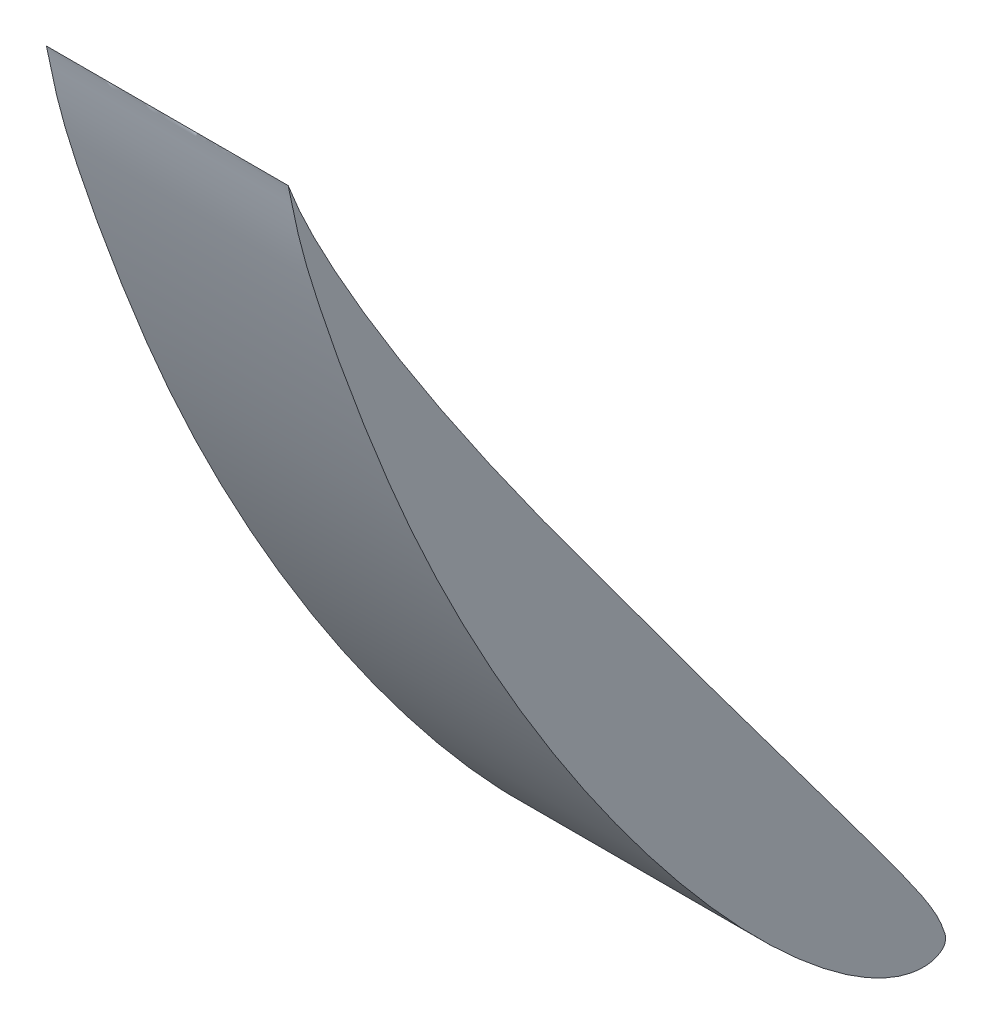
SolidWorks part; units mm, degrees
ref_plane "Front Plane" through (0, 0, 0) normal (0, 0, 1) x (1, 0, 0)
ref_plane "Top Plane" through (0, 0, 0) normal (0, 1, 0) x (1, 0, 0)
ref_plane "Right Plane" through (0, 0, 0) normal (1, 0, 0) x (0, 0, -1)
curve "Curve1"
  spline degree 3 poles (20, 28.4633, 15.8466) (20, 28.7145, 15.934) (20, 28.4668, 15.865) (20, 28.2665, 15.8303) (20, 27.805, 15.7338) (20, 27.257, 15.6261) (20, 26.5691, 15.4729) (20, 25.7774, 15.2676) (20, 24.8753, 15.0019) (20, 23.8666, 14.684) (20, 22.7562, 14.3166) (20, 21.5545, 13.9013) (20, 20.2714, 13.4406) (20, 18.9177, 12.9361) (20, 17.5049, 12.3899) (20, 16.0454, 11.8026) (20, 14.5502, 11.1748) (20, 13.0315, 10.4989) (20, 11.4963, 9.777) (20, 9.9507, 9.0131) (20, 8.4042, 8.2062) (20, 6.8625, 7.363) (20, 5.3341, 6.4857) (20, 3.8278, 5.5775) (20, 2.3494, 4.6458) (20, 0.9081, 3.6924) (20, -0.4896, 2.7237) (20, -1.8372, 1.7454) (20, -3.1273, 0.7627) (20, -4.3542, -0.2179) (20, -5.5115, -1.191) (20, -6.5931, -2.151) (20, -7.5948, -3.0911) (20, -8.5109, -4.0068) (20, -9.3378, -4.8917) (20, -10.0725, -5.7403) (20, -10.711, -6.5478) (20, -11.2536, -7.3075) (20, -11.6961, -8.0179) (20, -12.0372, -8.6743) (20, -12.2858, -9.2699) (20, -12.4349, -9.8062) (20, -12.4935, -10.273) (20, -12.4712, -10.6726) (20, -12.3544, -10.9815) (20, -12.1874, -11.2303) (20, -11.8784, -11.3083) (20, -11.5185, -11.187) (20, -11.0523, -11) (20, -10.4802, -10.6788) (20, -9.8012, -10.2446) (20, -9.0094, -9.6973) (20, -8.1049, -9.0458) (20, -7.0899, -8.2993) (20, -5.9699, -7.4667) (20, -4.7522, -6.5557) (20, -3.4437, -5.5759) (20, -2.0535, -4.5356) (20, -0.5903, -3.4444) (20, 0.9355, -2.3108) (20, 2.5131, -1.1441) (20, 4.1313, 0.0473) (20, 5.7779, 1.2578) (20, 7.4418, 2.4846) (20, 9.1179, 3.7188) (20, 10.8002, 4.9508) (20, 12.4834, 6.1624) (20, 14.1554, 7.3388) (20, 15.7997, 8.4713) (20, 17.4028, 9.5493) (20, 18.9517, 10.5634) (20, 20.4327, 11.5049) (20, 21.8324, 12.3661) (20, 23.1371, 13.1404) (20, 24.333, 13.822) (20, 25.4084, 14.4074) (20, 26.3458, 14.893) (20, 27.1456, 15.2804) (20, 27.7591, 15.5576) (20, 28.2613, 15.7594) (20, 28.4633, 15.8466) (20, 28.7145, 15.934) (20, 28.4668, 15.865) knots -0.008893 -0.003951 -0.000989 0 0.000979 0.003786 0.008179 0.01394 0.020915 0.029057 0.038414 0.048974 0.060645 0.073334 0.086939 0.101355 0.116471 0.132171 0.148332 0.16489 0.181807 0.198987 0.216369 0.233891 0.251455 0.26899 0.28641 0.303633 0.320589 0.337187 0.353353 0.369012 0.384083 0.3985 0.412191 0.425098 0.437171 0.448351 0.458606 0.467901 0.476216 0.483573 0.48997 0.495456 0.500132 0.503992 0.50723 0.509987 0.512501 0.516074 0.521095 0.527571 0.535587 0.545177 0.556302 0.568875 0.5828 0.597975 0.614286 0.631613 0.649826 0.668792 0.688371 0.708417 0.728797 0.749399 0.770146 0.790953 0.811664 0.832074 0.851999 0.871282 0.889761 0.90728 0.923686 0.938833 0.952579 0.964796 0.975365 0.984179 0.991107 0.996049 0.999011 1 1.000979 1.003786 1.008179 periodic
ref_plane "Plane1" through (20, 0, 0) normal (1, 0, 0) x (0, 0, -1)
sketch "Sketch2" plane through (20, 0, 0) normal (1, 0, 0) x (0, 0, -1)
  spline S0 degree 3 poles (-15.8466, 28.4633) (-15.934, 28.7145) (-15.865, 28.4668) (-15.8303, 28.2665) (-15.7338, 27.805) (-15.6261, 27.257) (-15.4729, 26.5691) (-15.2676, 25.7774) (-15.0019, 24.8753) (-14.684, 23.8666) (-14.3166, 22.7562) (-13.9013, 21.5545) (-13.4406, 20.2714) (-12.9361, 18.9177) (-12.3899, 17.5049) (-11.8026, 16.0454) (-11.1748, 14.5502) (-10.4989, 13.0315) (-9.777, 11.4963) (-9.0131, 9.9507) (-8.2062, 8.4042) (-7.363, 6.8625) (-6.4857, 5.3341) (-5.5775, 3.8278) (-4.6458, 2.3494) (-3.6924, 0.9081) (-2.7237, -0.4896) (-1.7454, -1.8372) (-0.7627, -3.1273) (0.2179, -4.3542) (1.191, -5.5115) (2.151, -6.5931) (3.0911, -7.5948) (4.0068, -8.5109) (4.8917, -9.3378) (5.7403, -10.0725) (6.5478, -10.711) (7.3075, -11.2536) (8.0179, -11.6961) (8.6743, -12.0372) (9.2699, -12.2858) (9.8062, -12.4349) (10.273, -12.4935) (10.6726, -12.4712) (10.9815, -12.3544) (11.2303, -12.1874) (11.3083, -11.8784) (11.187, -11.5185) (11, -11.0523) (10.6788, -10.4802) (10.2446, -9.8012) (9.6973, -9.0094) (9.0458, -8.1049) (8.2993, -7.0899) (7.4667, -5.9699) (6.5557, -4.7522) (5.5759, -3.4437) (4.5356, -2.0535) (3.4444, -0.5903) (2.3108, 0.9355) (1.1441, 2.5131) (-0.0473, 4.1313) (-1.2578, 5.7779) (-2.4846, 7.4418) (-3.7188, 9.1179) (-4.9508, 10.8002) (-6.1624, 12.4834) (-7.3388, 14.1554) (-8.4713, 15.7997) (-9.5493, 17.4028) (-10.5634, 18.9517) (-11.5049, 20.4327) (-12.3661, 21.8324) (-13.1404, 23.1371) (-13.822, 24.333) (-14.4074, 25.4084) (-14.893, 26.3458) (-15.2804, 27.1456) (-15.5576, 27.7591) (-15.7594, 28.2613) (-15.8466, 28.4633) (-15.934, 28.7145) (-15.865, 28.4668) knots -0.008893 -0.003951 -0.000989 0 0.000979 0.003786 0.008179 0.01394 0.020915 0.029057 0.038414 0.048974 0.060645 0.073334 0.086939 0.101355 0.116471 0.132171 0.148332 0.16489 0.181807 0.198987 0.216369 0.233891 0.251455 0.26899 0.28641 0.303633 0.320589 0.337187 0.353353 0.369012 0.384083 0.3985 0.412191 0.425098 0.437171 0.448351 0.458606 0.467901 0.476216 0.483573 0.48997 0.495456 0.500132 0.503992 0.50723 0.509987 0.512501 0.516074 0.521095 0.527571 0.535587 0.545177 0.556302 0.568875 0.5828 0.597975 0.614286 0.631613 0.649826 0.668792 0.688371 0.708417 0.728797 0.749399 0.770146 0.790953 0.811664 0.832074 0.851999 0.871282 0.889761 0.90728 0.923686 0.938833 0.952579 0.964796 0.975365 0.984179 0.991107 0.996049 0.999011 1 1.000979 1.003786 1.008179 only from (-15.9182, 28.6639) to (-15.9182, 28.6639) construction
  spline S1 degree 3 poles (-15.8466, 28.4633) (-15.934, 28.7145) (-15.865, 28.4668) (-15.8303, 28.2665) (-15.7338, 27.805) (-15.6261, 27.257) (-15.4729, 26.5691) (-15.2676, 25.7774) (-15.0019, 24.8753) (-14.684, 23.8666) (-14.3166, 22.7562) (-13.9013, 21.5545) (-13.4406, 20.2714) (-12.9361, 18.9177) (-12.3899, 17.5049) (-11.8026, 16.0454) (-11.1748, 14.5502) (-10.4989, 13.0315) (-9.777, 11.4963) (-9.0131, 9.9507) (-8.2062, 8.4042) (-7.363, 6.8625) (-6.4857, 5.3341) (-5.5775, 3.8278) (-4.6458, 2.3494) (-3.6924, 0.9081) (-2.7237, -0.4896) (-1.7454, -1.8372) (-0.7627, -3.1273) (0.2179, -4.3542) (1.191, -5.5115) (2.151, -6.5931) (3.0911, -7.5948) (4.0068, -8.5109) (4.8917, -9.3378) (5.7403, -10.0725) (6.5478, -10.711) (7.3075, -11.2536) (8.0179, -11.6961) (8.6743, -12.0372) (9.2699, -12.2858) (9.8062, -12.4349) (10.273, -12.4935) (10.6726, -12.4712) (10.9815, -12.3544) (11.2303, -12.1874) (11.3083, -11.8784) (11.187, -11.5185) (11, -11.0523) (10.6788, -10.4802) (10.2446, -9.8012) (9.6973, -9.0094) (9.0458, -8.1049) (8.2993, -7.0899) (7.4667, -5.9699) (6.5557, -4.7522) (5.5759, -3.4437) (4.5356, -2.0535) (3.4444, -0.5903) (2.3108, 0.9355) (1.1441, 2.5131) (-0.0473, 4.1313) (-1.2578, 5.7779) (-2.4846, 7.4418) (-3.7188, 9.1179) (-4.9508, 10.8002) (-6.1624, 12.4834) (-7.3388, 14.1554) (-8.4713, 15.7997) (-9.5493, 17.4028) (-10.5634, 18.9517) (-11.5049, 20.4327) (-12.3661, 21.8324) (-13.1404, 23.1371) (-13.822, 24.333) (-14.4074, 25.4084) (-14.893, 26.3458) (-15.2804, 27.1456) (-15.5576, 27.7591) (-15.7594, 28.2613) (-15.8466, 28.4633) (-15.934, 28.7145) (-15.865, 28.4668) knots -0.008893 -0.003951 -0.000989 0 0.000979 0.003786 0.008179 0.01394 0.020915 0.029057 0.038414 0.048974 0.060645 0.073334 0.086939 0.101355 0.116471 0.132171 0.148332 0.16489 0.181807 0.198987 0.216369 0.233891 0.251455 0.26899 0.28641 0.303633 0.320589 0.337187 0.353353 0.369012 0.384083 0.3985 0.412191 0.425098 0.437171 0.448351 0.458606 0.467901 0.476216 0.483573 0.48997 0.495456 0.500132 0.503992 0.50723 0.509987 0.512501 0.516074 0.521095 0.527571 0.535587 0.545177 0.556302 0.568875 0.5828 0.597975 0.614286 0.631613 0.649826 0.668792 0.688371 0.708417 0.728797 0.749399 0.770146 0.790953 0.811664 0.832074 0.851999 0.871282 0.889761 0.90728 0.923686 0.938833 0.952579 0.964796 0.975365 0.984179 0.991107 0.996049 0.999011 1 1.000979 1.003786 1.008179 only from (-15.9182, 28.6639) to (-15.9182, 28.6639)
extrude "Boss-Extrude1" add sketch "Sketch2" along normal blind 10
